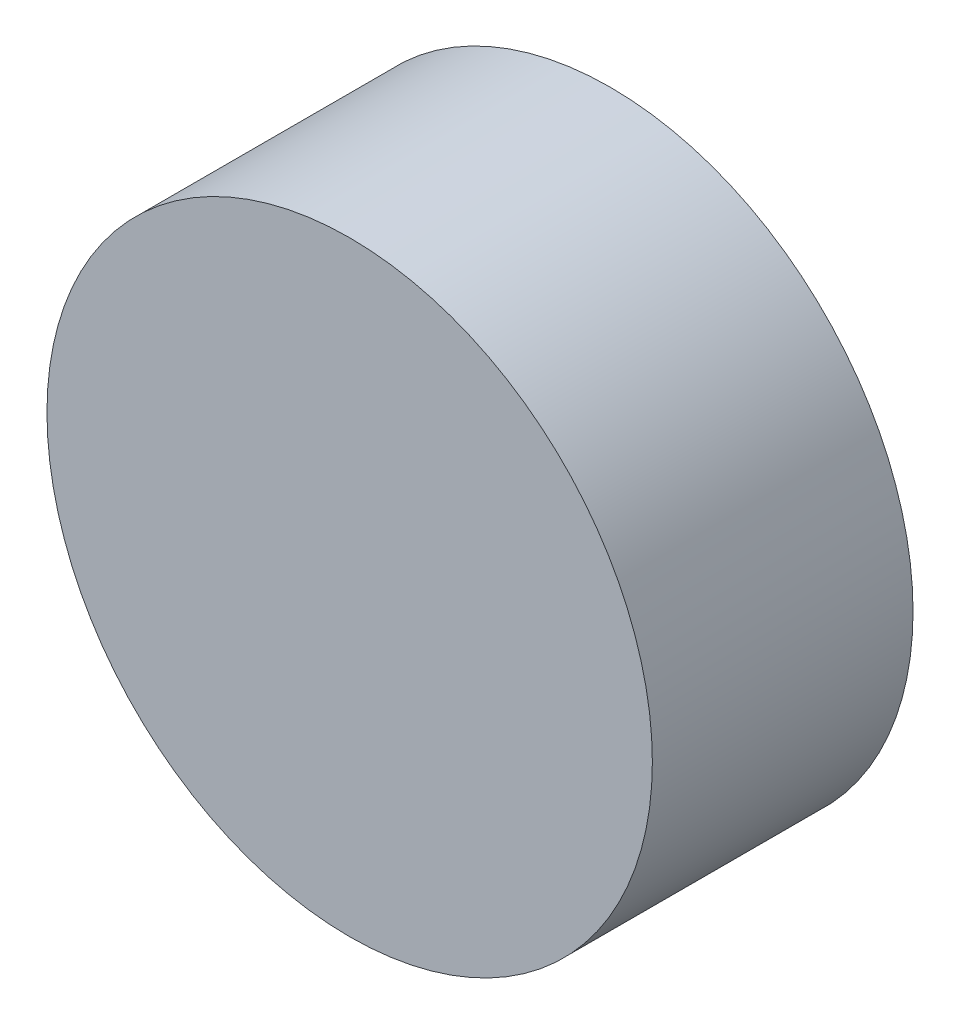
SolidWorks part; units mm, degrees
ref_plane "Ebene vorne" through (0, 0, 0) normal (0, 0, 1) x (1, 0, 0)
ref_plane "Ebene oben" through (0, 0, 0) normal (0, 1, 0) x (1, 0, 0)
ref_plane "Ebene rechts" through (0, 0, 0) normal (1, 0, 0) x (0, 0, -1)
sketch "Skizze1" plane through (0, 0, 0) normal (0, 1, 0) x (1, 0, 0)
  line L18 (0.0034, -8.0348) -> (0.0034, -10.0348)
  line L32 (20.9054, 7.9652) -> (18.9054, 7.9652)
  line L37 (0.0034, -10.0348) -> (20.9054, -10.0348)
  line L38 (0.0034, -8.0348) -> (18.9054, -8.0348)
  line L39 (20.9054, 7.9652) -> (20.9054, -10.0348)
  line L40 (18.9054, 7.9652) -> (18.9054, -2.0348)
  line L41 (18.9054, -2.0348) -> (17.4054, -2.0348)
  line L43 (17.4054, -4.0348) -> (18.9054, -4.0348)
  line L44 (18.9054, -4.0348) -> (18.9054, -8.0348)
  line L45 (17.4054, -2.0348) -> (17.4054, -4.0348)
revolve "Rotation2" add sketch "Skizze1" angle 360 about L18
